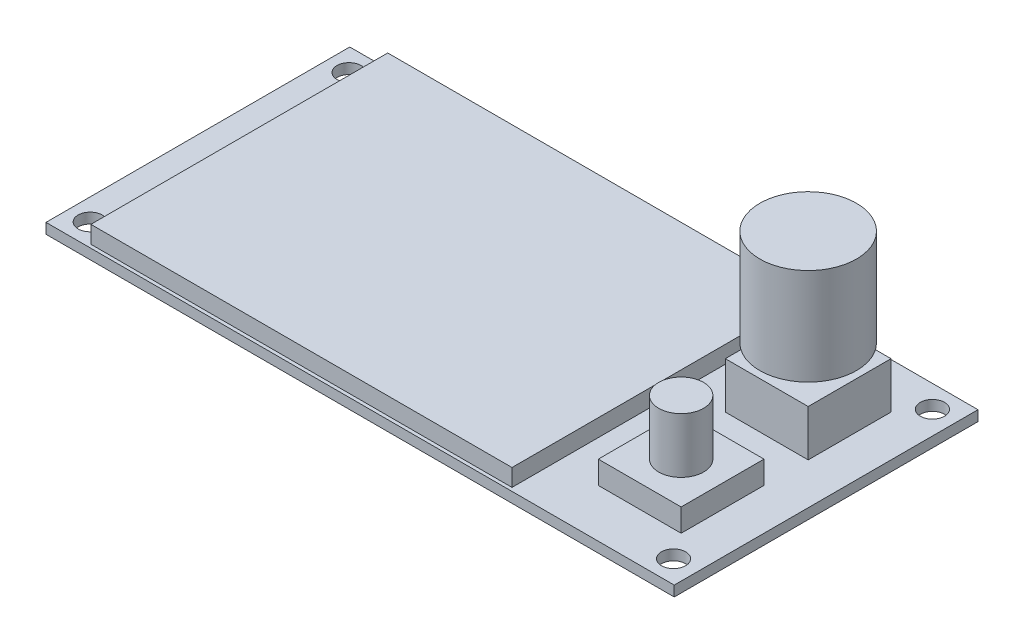
SolidWorks part; units mm, degrees
ref_plane "前视基准面" through (0, 0, 0) normal (0, 0, 1) x (1, 0, 0)
ref_plane "上视基准面" through (0, 0, 0) normal (0, 1, 0) x (1, 0, 0)
ref_plane "右视基准面" through (0, 0, 0) normal (1, 0, 0) x (0, 0, -1)
other "Configuration Table"
sketch "草图1" plane through (0, 0, 0) normal (0, 1, 0) x (1, 0, 0)
  line L0 (0, 0) -> (91, 0)
  line L1 (0, 0) -> (0, 44)
  line L2 (91, 0) -> (91, 44)
  line L3 (0, 44) -> (91, 44)
  dimension "D1" = 91
  dimension "D2" = 44
extrude "凸台-拉伸1" add sketch "草图1" along normal blind 1.5
sketch "草图2" plane through (0, 1.5, 0) normal (0, 1, 0) x (1, 0, 0)
  line L0 (0, 44) -> (0, 0) construction
  line L1 (6, 43.5) -> (67, 43.5)
  line L2 (6, 43.5) -> (6, 0.5)
  line L3 (6, 0.5) -> (67, 0.5)
  line L4 (67, 43.5) -> (67, 0.5)
  line L5 (91, 44) -> (0, 44) construction
  dimension "D1" = 61
  dimension "D2" = 43
  dimension "D3" = 67
  dimension "D4" = 0.5
extrude "凸台-拉伸2" add sketch "草图2" along normal blind 2.5
sketch "草图3" plane through (0, 1.5, 0) normal (0, 1, 0) x (1, 0, 0)
  line L0 (3.15, 5) -> (4.9152, 5) construction
  line L1 (3.15, 39) -> (4.9152, 39) construction
  line L3 (3.15, 1.5) -> (4.9, 1.5) construction
  line L5 (3.15, 42.5) -> (3.939, 42.5) construction
  line L6 (3.15, 1.5) -> (3.15, 0) construction
  line L7 (0, 0) -> (91, 0) construction
  line L8 (3.15, 42.5) -> (3.15, 44) construction
  line L9 (91, 44) -> (0, 44) construction
  line L10 (1.4, 40.75) -> (0, 40.75) construction
  line L11 (0, 44) -> (0, 0) construction
  line L12 (1.4, 3.25) -> (0, 3.25) construction
  line L13 (89.4, 40.75) -> (1.4, 40.75) construction
  line L14 (91, 0) -> (91, 44) construction
  line L15 (87.65, 1.5) -> (87.65, 0) construction
  line L16 (87.65, 42.5) -> (87.65, 44) construction
  line L17 (89.4, 40.75) -> (91, 40.75) construction
  line L18 (89.4, 3.25) -> (91, 3.25) construction
  circle A0 centre (87.65, 40.75) radius 1.75
  circle A1 centre (87.65, 3.25) radius 1.75
  circle A2 centre (3.15, 3.25) radius 1.75
  circle A3 centre (3.15, 40.75) radius 1.75
  point P38 (4.9, 1.5)
  dimension "D1" = 3.5
  dimension "D2" = 3.5
  dimension "D3" = 3.5
  dimension "D4" = 3.5
  dimension "D5" = 34
  dimension "D6" = 90
  dimension "D7" = 88
  dimension "D8" = 1.6
  dimension "D9" = 90
extrude "切除-拉伸1" cut sketch "草图3" against normal blind 2.5
sketch "草图4" plane through (0, 1.5, 0) normal (0, 1, 0) x (1, 0, 0)
  line L0 (0, 0) -> (91, 0) construction
  line L1 (73, 37.4) -> (85, 37.4)
  line L2 (73, 37.4) -> (73, 25.4)
  line L3 (73, 25.4) -> (85, 25.4)
  line L4 (85, 37.4) -> (85, 25.4)
  line L5 (73, 19) -> (85, 19)
  line L6 (73, 19) -> (73, 7)
  line L7 (73, 7) -> (85, 7)
  line L8 (85, 19) -> (85, 7)
  line L9 (91, 0) -> (91, 44) construction
  dimension "D1" = 12
  dimension "D2" = 12
  dimension "D3" = 12
  dimension "D4" = 6.4
  dimension "D5" = 19
  dimension "D6" = 18
  dimension "D7" = 18
extrude "凸台-拉伸3" add sketch "草图4" along normal blind 6.7
sketch "草图5" plane through (0, 8.2, 0) normal (0, 1, 0) x (1, 0, 0)
  line L0 (73, 19) -> (73, 7)
  line L1 (73, 7) -> (85, 7)
  line L2 (85, 7) -> (85, 19)
  line L3 (85, 19) -> (73, 19)
extrude "切除-拉伸2" cut sketch "草图5" against normal blind 3.4
sketch "草图6" plane through (0, 8.2, 0) normal (0, 1, 0) x (1, 0, 0)
  line L0 (73, 37.4) -> (85, 25.4) construction
  line L1 (73, 25.4) -> (79, 31.4) construction
  line L2 (73, 25.4) -> (85, 25.4) construction
  circle A0 centre (79, 31.4) radius 1
  dimension "D1" = 2
extrude "凸台-拉伸4" add sketch "草图6" along normal blind 2
sketch "草图7" plane through (0, 10.2, 0) normal (0, 1, 0) x (1, 0, 0)
  circle A0 centre (79, 31.4) radius 7
  dimension "D1" = 14
extrude "凸台-拉伸5" add sketch "草图7" along normal blind 14
sketch "草图8" plane through (0, 4.8, 0) normal (0, 1, 0) x (1, 0, 0)
  line L0 (73, 19) -> (73, 7) construction
  line L1 (73, 7) -> (85, 7) construction
  circle A0 centre (79, 13) radius 3.25
  point P6 (74.2895, 7)
  dimension "D1" = 6.5
  dimension "D2" = 6
  dimension "D3" = 6
extrude "凸台-拉伸6" add sketch "草图8" along normal blind 8
